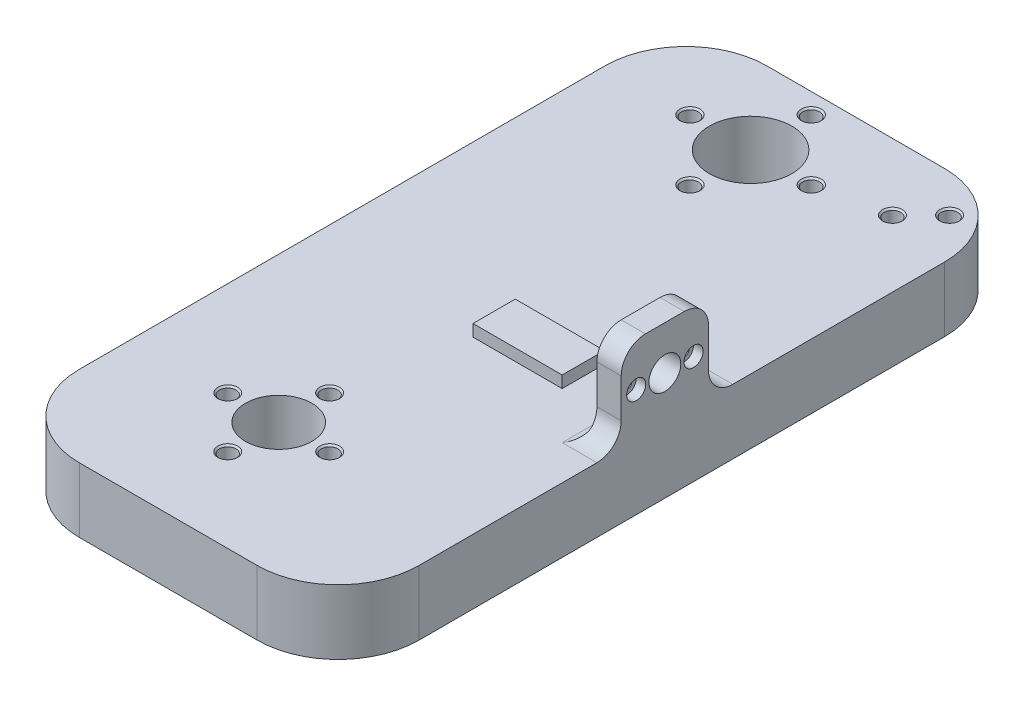
SolidWorks part; units mm, degrees
ref_plane "Front Plane" through (0, 0, 0) normal (0, 0, 1) x (1, 0, 0)
ref_plane "Top Plane" through (0, 0, 0) normal (0, 1, 0) x (1, 0, 0)
ref_plane "Right Plane" through (0, 0, 0) normal (1, 0, 0) x (0, 0, -1)
sketch "Sketch2" plane through (0, 0, 0) normal (0, 1, 0) x (1, 0, 0)
  line L0 (0, 74.1) -> (0, 0) construction
  line L1 (-22.86, -21.15) -> (30.48, -21.15)
  line L2 (-22.86, -21.15) -> (-22.86, 86.8)
  line L3 (-22.86, 86.8) -> (30.48, 86.8)
  line L4 (30.48, -21.15) -> (30.48, 86.8)
  circle A0 centre (0, 0) radius 5.207
  circle A1 centre (0, 74.1) radius 6.477
  dimension "D3" = 10.414
  dimension "D4" = 74.1
  dimension "D5" = 6.477
  dimension "D6" = 12.7
  dimension "D1" = 21.15
  dimension "D2" = 22.86
  dimension "D7" = 53.34
extrude "Boss-Extrude2" add sketch "Sketch2" along normal blind 10.16
sketch "Sketch14" plane through (0, 10.16, 0) normal (0, 1, 0) x (1, 0, 0)
  circle A0 centre (0, 74.1) radius 9.525 construction
  circle A1 centre (0, 83.625) radius 1.325
  circle A2 centre (-9.525, 74.1) radius 1.325
  circle A3 centre (9.525, 74.1) radius 1.325
  circle A4 centre (0, 64.575) radius 1.325
  dimension "D1" = 2.65
  dimension "D2" = 9.525
extrude "Cut-Extrude5" cut sketch "Sketch14" against normal through all
chamfer "Chamfer2" distance 0.254 angle 45 4 edges at (0, 10.16, -63.25) (9.525, 10.16, -72.775) (-9.525, 10.16, -72.775) (0, 10.16, -82.3)
hole_wizard "Ø2.6 (2.6) Diameter Hole1" positions "Sketch3" profile "Sketch4" hole size "Ø2.6" standard "ANSI Metric" end condition through all
sketch "Sketch3" plane through (0, 10.16, 0) normal (0, 1, 0) x (1, 0, 0)
  circle A0 centre (0, 0) radius 8 construction
  point P5 (0, 8)
  point P7 (8, 0)
  point P9 (0, -8)
  point P11 (-8, 0)
  dimension "D1" = 16
sketch "Sketch4" plane through (-8, 10.16, 0) normal (1, 0, 0) x (0, 0, 1)
  line L0 (0, 0) -> (0, 10.16)
  line L1 (0, 10.16) -> (1.3, 10.16)
  line L2 (1.3, 10.16) -> (1.3, 0)
  line L5 (1.3, 0) -> (0, 0)
  line L11 (0, -6.35) -> (0, 107.95) construction
  dimension "Thru Hole Dia." = 2.6
  dimension "Thru Hole Depth" = 10.16
sketch "Sketch5" plane through (30.48, 0, 0) normal (1, 0, 0) x (0, 0, -1)
  line L0 (-21.15, 10.16) -> (86.8, 10.16) construction
  line L1 (23.3, 10.16) -> (37.016, 10.16)
  line L2 (23.3, 10.16) -> (23.3, 23.876)
  line L3 (23.3, 23.876) -> (37.016, 23.876)
  line L4 (37.016, 10.16) -> (37.016, 23.876)
  line L5 (23.3, 17.018) -> (37.016, 17.018) construction
  line L6 (30.158, 17.018) -> (30.158, 10.16) construction
  line L7 (-21.15, 10.16) -> (-21.15, 0) construction
  circle A0 centre (25.658, 17.018) radius 0.85
  circle A1 centre (34.658, 17.018) radius 0.85
  circle A2 centre (30.158, 17.018) radius 2.5
  dimension "D3" = 1.7
  dimension "D4" = 4.5
  dimension "D5" = 5
  dimension "D1" = 13.716
  dimension "D2" = 13.716
  dimension "D6" = 44.45
extrude "Boss-Extrude3" add sketch "Sketch5" against normal blind 3.81
sketch "Sketch6" plane through (30.48, 0, 0) normal (1, 0, 0) x (0, 0, -1)
  circle A0 centre (25.658, 17.018) radius 1.5
  circle A1 centre (34.658, 17.018) radius 1.5
  circle A3 centre (34.658, 17.018) radius 0.85 construction
  dimension "D1" = 3
extrude "Cut-Extrude1" cut sketch "Sketch6" against normal blind 1.5
sketch "Sketch7" plane through (0, 10.16, 0) normal (0, 1, 0) x (1, 0, 0)
  line L0 (26.67, 23.3) -> (26.67, 37.016) construction
  line L1 (17.67, 33.4746) -> (3.6698, 33.4746)
  line L2 (17.67, 33.4746) -> (17.67, 26.8414)
  line L3 (17.67, 26.8414) -> (3.6698, 26.8414)
  line L4 (3.6698, 33.4746) -> (3.6698, 26.8414)
  line L5 (26.67, 30.158) -> (17.67, 30.158) construction
  dimension "D1" = 9
  dimension "D2" = 14.0002
  dimension "D3" = 6.6332
extrude "Boss-Extrude4" add sketch "Sketch7" along normal blind 1.8542
fillet "Fillet1" radius 12.7 4 edges at (30.48, 5.08, -86.8) (-22.86, 5.08, -86.8) (30.48, 5.08, 21.15) (-22.86, 5.08, 21.15)
fillet "Fillet2" radius 3.81 4 edges at (28.575, 10.16, -37.016) (28.575, 23.876, -37.016) (28.575, 23.876, -23.3) (28.575, 10.16, -23.3)
fillet "Fillet3" radius 1.651 1 edges at (26.67, 10.16, -30.158)
sketch "Sketch13" plane through (0, 10.16, 0) normal (0, 1, 0) x (1, 0, 0)
  line L0 (17.78, 74.1) -> (26.7603, 83.0803) construction
  circle A0 centre (24.5152, 80.8352) radius 1.3
  circle A1 centre (20.0251, 76.3451) radius 1.3
  arc A2 (30.48, 74.1) -> (17.78, 86.8) centre (17.78, 74.1) ccw construction
  arc A3 (30.48, 74.1) -> (17.78, 86.8) centre (17.78, 74.1) ccw construction
  dimension "D1" = 2.6
  dimension "D3" = 6.35
  dimension "D4" = 3.175
  dimension "D2" = 45
extrude "Cut-Extrude4" cut sketch "Sketch13" against normal through all
chamfer "Chamfer3" distance 0.254 angle 45 2 edges at (24.5152, 10.16, -79.5352) (20.0251, 10.16, -75.0451)
chamfer "Chamfer1" distance 0.254 angle 45 4 edges at (0, 10.16, 9.3) (8, 10.16, 1.3) (0, 10.16, -6.7) (-8, 10.16, 1.3)
sketch "Sketch16" plane through (0, 0, 0) normal (0, -1, 0) x (1, 0, 0)
  line L0 (30.48, -32.658) -> (30.48, -27.658) construction
  line L1 (30.48, -32.658) -> (30.48, -27.658) construction
  line L2 (30.48, -30.158) -> (15.24, -30.158) construction
  line L3 (15.24, -30.158) -> (7.62, -30.158) construction
  circle A0 centre (15.24, -30.158) radius 1.325
  circle A1 centre (7.62, -30.158) radius 1.325
  dimension "D1" = 2.65
  dimension "D2" = 7.62
  dimension "D3" = 15.24
extrude "Cut-Extrude6" cut sketch "Sketch16" against normal blind 8.255
chamfer "Chamfer4" distance 0.254 angle 45 2 edges at (15.24, 0, -31.483) (7.62, 0, -31.483)
